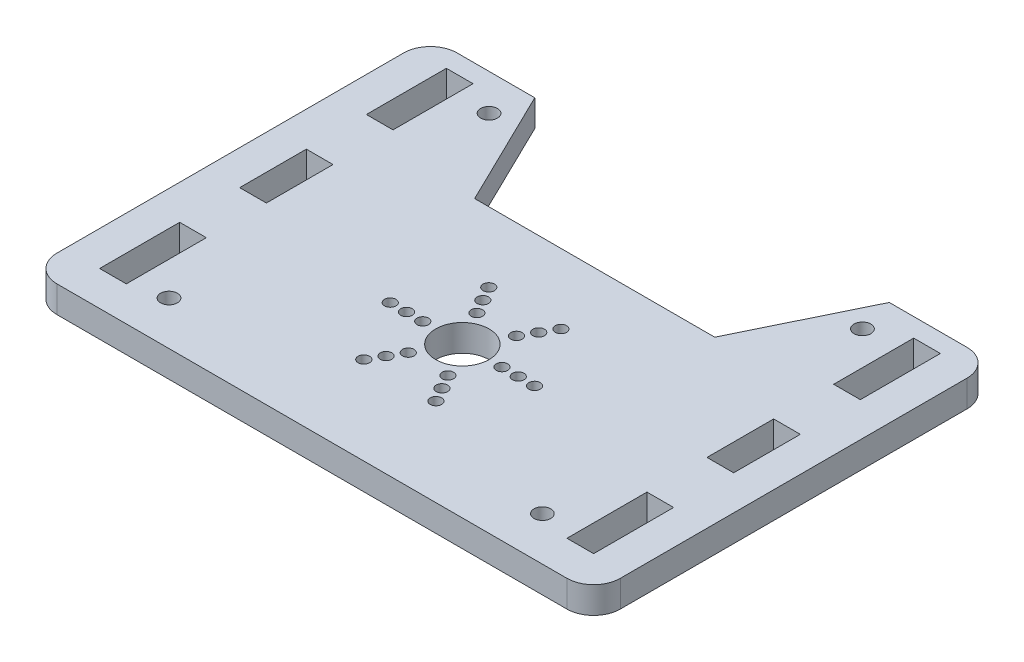
SolidWorks part; units mm, degrees
ref_plane "前视基准面" through (0, 0, 0) normal (0, 0, 1) x (1, 0, 0)
ref_plane "上视基准面" through (0, 0, 0) normal (0, 1, 0) x (1, 0, 0)
ref_plane "右视基准面" through (0, 0, 0) normal (1, 0, 0) x (0, 0, -1)
sketch "草图1" plane through (0, 0, 0) normal (0, 1, 0) x (1, 0, 0)
  line L0 (-495.9605, 0) -> (24504.0395, 0) construction
  line L1 (0, -500) -> (0, 24500) construction
  line L2 (52.8, -28.1971) -> (-52.8, -28.1971)
  line L3 (-52.8, -28.1971) -> (-52.8, 46.8029)
  line L4 (-52.8, 46.8029) -> (-33.2301, 46.8029)
  line L5 (-33.2301, 46.8029) -> (-22.5, 24.8029)
  line L6 (-22.5, 24.8029) -> (22.5, 24.8029)
  line L7 (-22.5, 24.8029) -> (-39.3984, 24.8029) construction
  line L8 (-46.3, 43.3029) -> (-41.3, 43.3029)
  line L9 (-46.3, 43.3029) -> (-46.3, 28.3029)
  line L10 (-46.3, 28.3029) -> (-41.3, 28.3029)
  line L11 (-41.3, 43.3029) -> (-41.3, 28.3029)
  line L12 (-46.3, 17.0529) -> (-41.3, 17.0529)
  line L13 (-46.3, 17.0529) -> (-46.3, 4.5529)
  line L14 (-46.3, 4.5529) -> (-41.3, 4.5529)
  line L15 (-41.3, 17.0529) -> (-41.3, 4.5529)
  line L16 (-46.3, -6.6971) -> (-41.3, -6.6971)
  line L17 (-46.3, -6.6971) -> (-46.3, -21.6971)
  line L18 (-46.3, -21.6971) -> (-41.3, -21.6971)
  line L19 (-41.3, -6.6971) -> (-41.3, -21.6971)
  line L20 (46.3, -21.6971) -> (41.3, -21.6971)
  line L21 (46.3, -6.6971) -> (41.3, -6.6971)
  line L22 (46.3, -6.6971) -> (46.3, -21.6971)
  line L23 (46.3, 4.5529) -> (41.3, 4.5529)
  line L24 (41.3, 17.0529) -> (41.3, 4.5529)
  line L25 (46.3, 17.0529) -> (41.3, 17.0529)
  line L26 (46.3, 17.0529) -> (46.3, 4.5529)
  line L27 (46.3, 28.3029) -> (41.3, 28.3029)
  line L28 (46.3, 43.3029) -> (41.3, 43.3029)
  line L29 (41.3, 43.3029) -> (41.3, 28.3029)
  line L30 (46.3, 43.3029) -> (46.3, 28.3029)
  line L31 (52.8, -28.1971) -> (52.8, 46.8029)
  line L32 (52.8, 46.8029) -> (33.2301, 46.8029)
  line L33 (33.2301, 46.8029) -> (22.5, 24.8029)
  line L34 (41.3, -6.6971) -> (41.3, -21.6971)
  circle A0 centre (0, 0) radius 5
  circle A1 centre (-13.525, 0) radius 1.075
  circle A2 centre (-10.475, 0) radius 1.075
  circle A3 centre (-7.425, 0) radius 1.075
  circle A4 centre (-6.7625, 11.713) radius 1.075
  circle A5 centre (-5.2375, 9.0716) radius 1.075
  circle A6 centre (-3.7125, 6.4302) radius 1.075
  circle A7 centre (6.7625, 11.713) radius 1.075
  circle A8 centre (5.2375, 9.0716) radius 1.075
  circle A9 centre (3.7125, 6.4302) radius 1.075
  circle A10 centre (13.525, 0) radius 1.075
  circle A11 centre (10.475, 0) radius 1.075
  circle A12 centre (7.425, 0) radius 1.075
  circle A13 centre (6.7625, -11.713) radius 1.075
  circle A14 centre (5.2375, -9.0716) radius 1.075
  circle A15 centre (3.7125, -6.4302) radius 1.075
  circle A16 centre (-6.7625, -11.713) radius 1.075
  circle A17 centre (-5.2375, -9.0716) radius 1.075
  circle A18 centre (-3.7125, -6.4302) radius 1.075
  circle A20 centre (-35, -20) radius 1.575
  circle A21 centre (-35, 40) radius 1.575
  circle A22 centre (35, 40) radius 1.575
  circle A23 centre (35, -20) radius 1.575
  point P46 (0, 0)
  point P84 (0, -28.1971)
  point P87 (0, 24.8029)
  dimension "D1" = 2.15
  dimension "D2" = 10
  dimension "D18" = 20
  dimension "D19" = 3.15
  dimension "D21" = 3.15
  dimension "D3" = 27.05
  dimension "D4" = 3.05
  dimension "D5" = 3.05
  dimension "D7" = 105.6
  dimension "D8" = 75
  dimension "D9" = 45
  dimension "D10" = 15
  dimension "D11" = 3.5
  dimension "D12" = 11.25
  dimension "D13" = 12.5
  dimension "D14" = 11.25
  dimension "D15" = 15
  dimension "D16" = 5
  dimension "D17" = 53
  dimension "D20" = 40
  dimension "D22" = 35
  dimension "D23" = 64
  dimension "D24" = 6.5
  dimension "D6" = 6
extrude "凸台-拉伸1" add sketch "草图1" along normal blind 5
fillet "圆角1" radius 5 4 edges at (52.8, 2.5, 28.1971) (52.8, 2.5, -46.8029) (-52.8, 2.5, -46.8029) (-52.8, 2.5, 28.1971)
